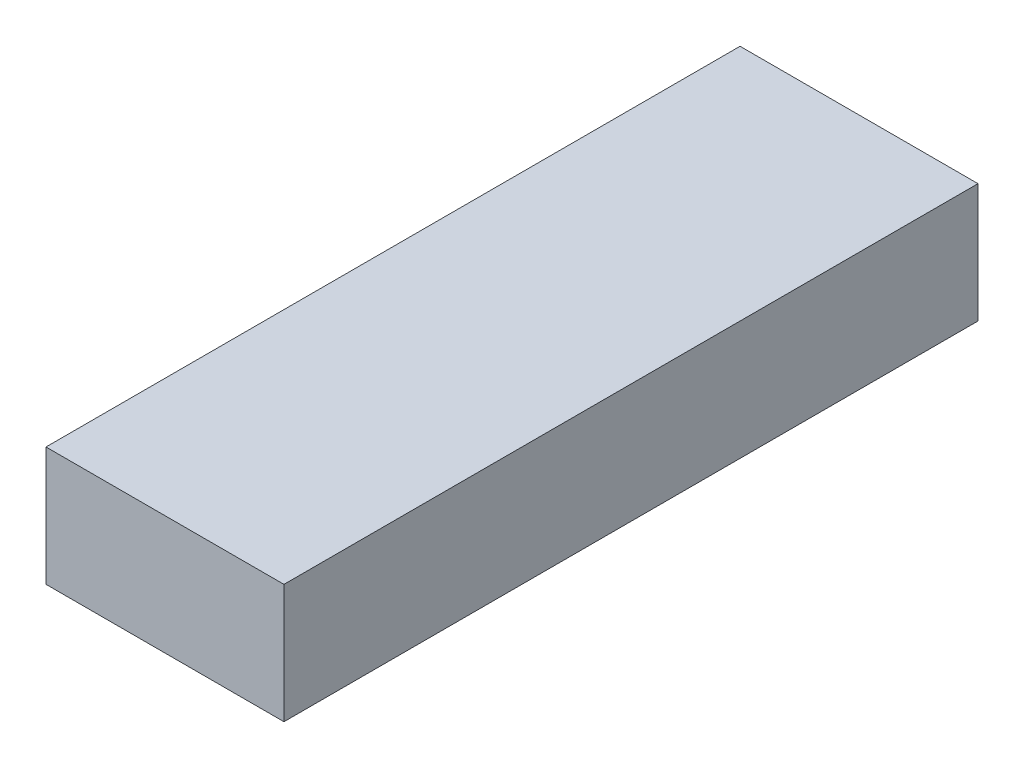
SolidWorks part; units mm, degrees
ref_plane "Front Plane" through (0, 0, 0) normal (0, 0, 1) x (1, 0, 0)
ref_plane "Top Plane" through (0, 0, 0) normal (0, 1, 0) x (1, 0, 0)
ref_plane "Right Plane" through (0, 0, 0) normal (1, 0, 0) x (0, 0, -1)
sketch "Sketch1" plane through (0, 0, 0) normal (0, 0, 1) x (1, 0, 0)
  line L1 (-7.9124, 5.0669) -> (7.3276, 5.0669)
  line L2 (-7.9124, 5.0669) -> (-7.9124, -2.5531)
  line L3 (-7.9124, -2.5531) -> (7.3276, -2.5531)
  line L4 (7.3276, 5.0669) -> (7.3276, -2.5531)
  dimension "D1" = 15.24
  dimension "D2" = 7.62
extrude "Boss-Extrude1" add sketch "Sketch1" along normal blind 44.45
